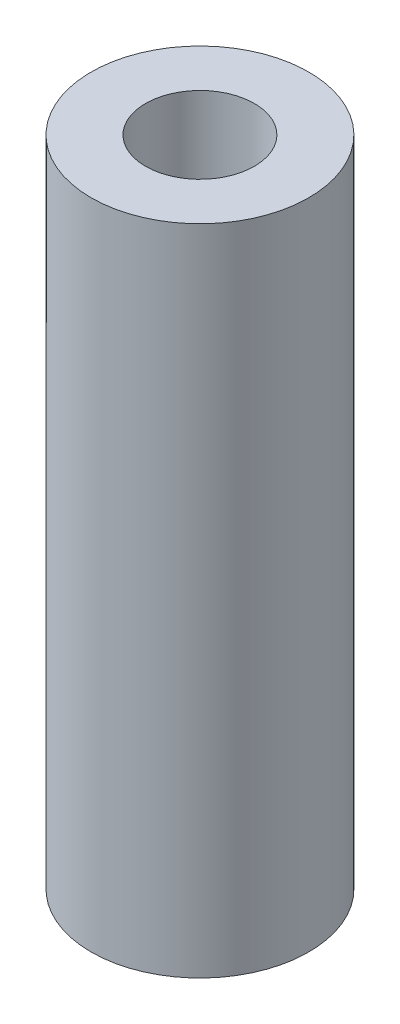
SolidWorks part; units mm, degrees
ref_plane "Front Plane" through (0, 0, 0) normal (0, 0, 1) x (1, 0, 0)
ref_plane "Top Plane" through (0, 0, 0) normal (0, 1, 0) x (1, 0, 0)
ref_plane "Right Plane" through (0, 0, 0) normal (1, 0, 0) x (0, 0, -1)
sketch "Sketch1" plane through (0, 0, 0) normal (0, 1, 0) x (1, 0, 0)
  circle A0 centre (0, 0) radius 2.5
  circle A1 centre (0, 0) radius 1.25
  dimension "D1" = 2.5
  dimension "D2" = 5
extrude "Boss-Extrude1" add sketch "Sketch1" along normal blind 15
